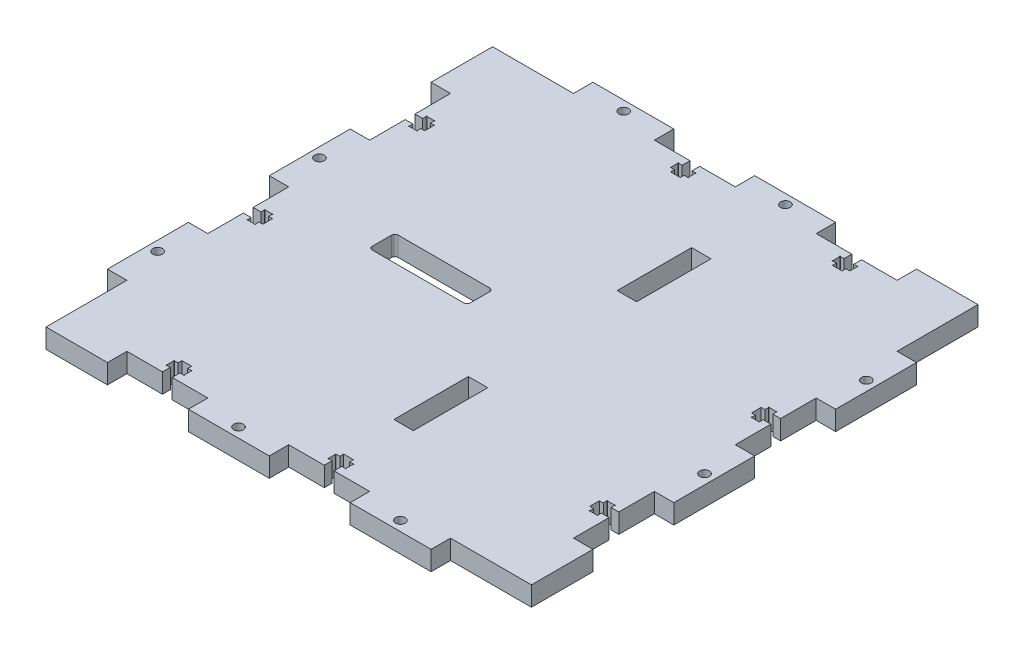
SolidWorks part; units mm, degrees
ref_plane "Front Plane" through (0, 0, 0) normal (0, 0, 1) x (1, 0, 0)
ref_plane "Top Plane" through (0, 0, 0) normal (0, 1, 0) x (1, 0, 0)
ref_plane "Right Plane" through (0, 0, 0) normal (1, 0, 0) x (0, 0, -1)
sketch "Sketch1" plane through (0, 0, 0) normal (0, 1, 0) x (1, 0, 0)
  line L0 (0, 75) -> (25, 75)
  line L1 (-50, 75) -> (-25, 75)
  line L2 (-75, 69) -> (-75, 50)
  line L3 (-69, -75) -> (-50, -75)
  line L4 (75, 50) -> (75, 25)
  line L7 (-75, 69) -> (-50, 69)
  line L8 (-50, 75) -> (-50, 69)
  line L10 (-25, 75) -> (-25, 69)
  line L11 (-25, 69) -> (0, 69)
  line L12 (0, 75) -> (0, 69)
  line L13 (50, 75) -> (69, 75)
  line L15 (25, 75) -> (25, 69)
  line L16 (25, 69) -> (50, 69)
  line L17 (50, 75) -> (50, 69)
  line L18 (75, 0) -> (75, -25)
  line L21 (75, 50) -> (69, 50)
  line L22 (69, 75) -> (69, 50)
  line L23 (75, 25) -> (69, 25)
  line L25 (75, 0) -> (69, 0)
  line L26 (69, 25) -> (69, 0)
  line L27 (75, -25) -> (69, -25)
  line L29 (75, -50) -> (69, -50)
  line L30 (69, -25) -> (69, -50)
  line L31 (75, -50) -> (75, -69)
  line L32 (25, -75) -> (50, -75)
  line L35 (75, -69) -> (50, -69)
  line L36 (50, -75) -> (50, -69)
  line L38 (25, -75) -> (25, -69)
  line L39 (25, -69) -> (0, -69)
  line L40 (0, -75) -> (0, -69)
  line L42 (-25, -75) -> (-25, -69)
  line L43 (-25, -69) -> (-50, -69)
  line L44 (-50, -75) -> (-50, -69)
  line L45 (-25, -75) -> (0, -75)
  line L46 (-75, 25) -> (-75, 0)
  line L49 (-75, -50) -> (-69, -50)
  line L50 (-69, -75) -> (-69, -50)
  line L51 (-75, -25) -> (-69, -25)
  line L53 (-75, 0) -> (-69, 0)
  line L54 (-69, -25) -> (-69, 0)
  line L55 (-75, 25) -> (-69, 25)
  line L57 (-75, 50) -> (-69, 50)
  line L58 (-69, 25) -> (-69, 50)
  line L59 (-75, -25) -> (-75, -50)
  dimension "D1" = 150
  dimension "D2" = 150
  dimension "D3" = 25
  dimension "D4" = 6
  dimension "D5" = 25
  dimension "25" = 25
  dimension "D6" = 25
  dimension "D7" = 6
  dimension "D8" = 6
  dimension "D9" = 25
  dimension "D10" = 25
  dimension "D11" = 6
  dimension "D12" = 25
  dimension "D13" = 6
  dimension "D14" = 25
  dimension "D15" = 25
  dimension "D16" = 6
  dimension "D17" = 25
  dimension "D18" = 19
  dimension "D19" = 6
  dimension "D20" = 25
  dimension "D21" = 25
  dimension "D22" = 25
  dimension "D23" = 6
  dimension "D24" = 6
  dimension "D25" = 25
  dimension "D26" = 25
  dimension "D27" = 19
  dimension "D28" = 6
  dimension "D29" = 25
  dimension "D30" = 25
  dimension "D31" = 6
  dimension "D32" = 25
  dimension "D33" = 25
  dimension "D34" = 6
  dimension "D35" = 25
  dimension "D36" = 19
extrude "Boss-Extrude1" add sketch "Sketch1" along normal blind 6
sketch "Sketch2" plane through (0, 6, 0) normal (0, 1, 0) x (1, 0, 0)
  line L0 (-25, 75) -> (-50, 75) construction
  line L1 (-25, 69) -> (-25, 75) construction
  line L2 (25, 75) -> (0, 75) construction
  line L3 (25, 69) -> (25, 75) construction
  line L4 (75, 25) -> (75, 50) construction
  line L5 (75, 50) -> (69, 50) construction
  line L6 (75, -25) -> (75, 0) construction
  line L7 (75, 0) -> (69, 0) construction
  line L8 (25, -75) -> (50, -75) construction
  line L9 (50, -75) -> (50, -69) construction
  line L10 (-25, -75) -> (0, -75) construction
  line L11 (0, -75) -> (0, -69) construction
  line L12 (-69, -25) -> (-75, -25) construction
  line L13 (-75, -25) -> (-75, -50) construction
  line L14 (-75, 25) -> (-75, 0) construction
  line L15 (-75, 0) -> (-69, 0) construction
  line L16 (-11, 69) -> (-14, 69)
  line L59 (0, 69) -> (-25, 69) construction
  line L60 (-14, 69) -> (-14, 66.6)
  line L61 (-14, 66.6) -> (-15.1, 66.6)
  line L63 (-15.2, 66.5) -> (-15.2, 64.3)
  line L65 (-15.1, 64.2) -> (-14, 64.2)
  line L66 (-14, 64.2) -> (-14, 63)
  line L67 (-14, 63) -> (-11, 63)
  line L69 (-12.5, 69) -> (-12.5, 63) construction
  line L72 (-11, 64.2) -> (-11, 63)
  line L73 (-9.9, 64.2) -> (-11, 64.2)
  line L74 (-9.8, 66.5) -> (-9.8, 64.3)
  line L75 (-11, 66.6) -> (-9.9, 66.6)
  line L76 (-11, 69) -> (-11, 66.6)
  line L91 (69, 11) -> (69, 14)
  line L92 (69, 14) -> (66.6, 14)
  line L93 (66.6, 14) -> (66.6, 15.1)
  line L94 (66.5, 15.2) -> (64.3, 15.2)
  line L95 (64.2, 15.1) -> (64.2, 14)
  line L96 (64.2, 14) -> (63, 14)
  line L97 (63, 14) -> (63, 11)
  line L98 (69, 12.5) -> (63, 12.5) construction
  line L99 (64.2, 11) -> (63, 11)
  line L100 (64.2, 9.9) -> (64.2, 11)
  line L101 (66.5, 9.8) -> (64.3, 9.8)
  line L102 (66.6, 11) -> (66.6, 9.9)
  line L103 (69, 11) -> (66.6, 11)
  line L104 (69, 0) -> (69, 25) construction
  line L105 (39, 69) -> (36, 69)
  line L106 (36, 69) -> (36, 66.6)
  line L107 (36, 66.6) -> (34.9, 66.6)
  line L108 (34.8, 66.5) -> (34.8, 64.3)
  line L109 (34.9, 64.2) -> (36, 64.2)
  line L110 (36, 64.2) -> (36, 63)
  line L111 (36, 63) -> (39, 63)
  line L112 (37.5, 69) -> (37.5, 63) construction
  line L113 (39, 64.2) -> (39, 63)
  line L114 (40.1, 64.2) -> (39, 64.2)
  line L115 (40.2, 66.5) -> (40.2, 64.3)
  line L116 (39, 66.6) -> (40.1, 66.6)
  line L117 (39, 69) -> (39, 66.6)
  line L118 (50, 69) -> (25, 69) construction
  line L119 (69, -39) -> (69, -36)
  line L120 (69, -36) -> (66.6, -36)
  line L121 (66.6, -36) -> (66.6, -34.9)
  line L122 (66.5, -34.8) -> (64.3, -34.8)
  line L123 (64.2, -34.9) -> (64.2, -36)
  line L124 (64.2, -36) -> (63, -36)
  line L125 (63, -36) -> (63, -39)
  line L126 (69, -37.5) -> (63, -37.5) construction
  line L127 (64.2, -39) -> (63, -39)
  line L128 (64.2, -40.1) -> (64.2, -39)
  line L129 (66.5, -40.2) -> (64.3, -40.2)
  line L130 (66.6, -39) -> (66.6, -40.1)
  line L131 (69, -39) -> (66.6, -39)
  line L132 (69, -50) -> (69, -25) construction
  line L133 (11, -69) -> (14, -69)
  line L134 (14, -69) -> (14, -66.6)
  line L135 (14, -66.6) -> (15.1, -66.6)
  line L136 (15.2, -66.5) -> (15.2, -64.3)
  line L137 (15.1, -64.2) -> (14, -64.2)
  line L138 (14, -64.2) -> (14, -63)
  line L139 (14, -63) -> (11, -63)
  line L140 (12.5, -69) -> (12.5, -63) construction
  line L141 (11, -64.2) -> (11, -63)
  line L142 (9.9, -64.2) -> (11, -64.2)
  line L143 (9.8, -66.5) -> (9.8, -64.3)
  line L144 (11, -66.6) -> (9.9, -66.6)
  line L145 (11, -69) -> (11, -66.6)
  line L146 (0, -69) -> (25, -69) construction
  line L147 (-39, -69) -> (-36, -69)
  line L148 (-36, -69) -> (-36, -66.6)
  line L149 (-36, -66.6) -> (-34.9, -66.6)
  line L150 (-34.8, -66.5) -> (-34.8, -64.3)
  line L151 (-34.9, -64.2) -> (-36, -64.2)
  line L152 (-36, -64.2) -> (-36, -63)
  line L153 (-36, -63) -> (-39, -63)
  line L154 (-37.5, -69) -> (-37.5, -63) construction
  line L155 (-39, -64.2) -> (-39, -63)
  line L156 (-40.1, -64.2) -> (-39, -64.2)
  line L157 (-40.2, -66.5) -> (-40.2, -64.3)
  line L158 (-39, -66.6) -> (-40.1, -66.6)
  line L159 (-39, -69) -> (-39, -66.6)
  line L160 (-50, -69) -> (-25, -69) construction
  line L161 (-69, 39) -> (-69, 36)
  line L162 (-69, 36) -> (-66.6, 36)
  line L163 (-66.6, 36) -> (-66.6, 34.9)
  line L164 (-66.5, 34.8) -> (-64.3, 34.8)
  line L165 (-64.2, 34.9) -> (-64.2, 36)
  line L166 (-64.2, 36) -> (-63, 36)
  line L167 (-63, 36) -> (-63, 39)
  line L168 (-69, 37.5) -> (-63, 37.5) construction
  line L169 (-64.2, 39) -> (-63, 39)
  line L170 (-64.2, 40.1) -> (-64.2, 39)
  line L171 (-66.5, 40.2) -> (-64.3, 40.2)
  line L172 (-66.6, 39) -> (-66.6, 40.1)
  line L173 (-69, 39) -> (-66.6, 39)
  line L174 (-69, 50) -> (-69, 25) construction
  line L175 (-69, -11) -> (-69, -14)
  line L176 (-69, -14) -> (-66.6, -14)
  line L177 (-66.6, -14) -> (-66.6, -15.1)
  line L178 (-66.5, -15.2) -> (-64.3, -15.2)
  line L179 (-64.2, -15.1) -> (-64.2, -14)
  line L180 (-64.2, -14) -> (-63, -14)
  line L181 (-63, -14) -> (-63, -11)
  line L182 (-69, -12.5) -> (-63, -12.5) construction
  line L183 (-64.2, -11) -> (-63, -11)
  line L184 (-64.2, -9.9) -> (-64.2, -11)
  line L185 (-66.5, -9.8) -> (-64.3, -9.8)
  line L186 (-66.6, -11) -> (-66.6, -9.9)
  line L187 (-69, -11) -> (-66.6, -11)
  line L188 (-69, 0) -> (-69, -25) construction
  circle A0 centre (-37.5, 72) radius 1.5
  circle A1 centre (12.5, 72) radius 1.5
  circle A2 centre (72, 37.5) radius 1.5
  circle A3 centre (72, -12.5) radius 1.5
  circle A4 centre (37.5, -72) radius 1.5
  circle A5 centre (-12.5, -72) radius 1.5
  circle A6 centre (-72, -37.5) radius 1.5
  circle A7 centre (-72, 12.5) radius 1.5
  arc A9 (-15.1, 66.6) -> (-15.2, 66.5) centre (-15.2, 66.6) ccw
  arc A10 (-15.2, 64.3) -> (-15.1, 64.2) centre (-15.2, 64.2) ccw
  arc A11 (-9.8, 64.3) -> (-9.9, 64.2) centre (-9.8, 64.2) cw
  arc A12 (-9.9, 66.6) -> (-9.8, 66.5) centre (-9.8, 66.6) cw
  arc A17 (66.6, 15.1) -> (66.5, 15.2) centre (66.6, 15.2) ccw
  arc A18 (64.3, 15.2) -> (64.2, 15.1) centre (64.2, 15.2) ccw
  arc A19 (64.3, 9.8) -> (64.2, 9.9) centre (64.2, 9.8) cw
  arc A20 (66.6, 9.9) -> (66.5, 9.8) centre (66.6, 9.8) cw
  arc A21 (34.9, 66.6) -> (34.8, 66.5) centre (34.8, 66.6) ccw
  arc A22 (34.8, 64.3) -> (34.9, 64.2) centre (34.8, 64.2) ccw
  arc A23 (40.2, 64.3) -> (40.1, 64.2) centre (40.2, 64.2) cw
  arc A24 (40.1, 66.6) -> (40.2, 66.5) centre (40.2, 66.6) cw
  arc A25 (66.6, -34.9) -> (66.5, -34.8) centre (66.6, -34.8) ccw
  arc A26 (64.3, -34.8) -> (64.2, -34.9) centre (64.2, -34.8) ccw
  arc A27 (64.3, -40.2) -> (64.2, -40.1) centre (64.2, -40.2) cw
  arc A28 (66.6, -40.1) -> (66.5, -40.2) centre (66.6, -40.2) cw
  arc A29 (15.1, -66.6) -> (15.2, -66.5) centre (15.2, -66.6) ccw
  arc A30 (15.2, -64.3) -> (15.1, -64.2) centre (15.2, -64.2) ccw
  arc A31 (9.8, -64.3) -> (9.9, -64.2) centre (9.8, -64.2) cw
  arc A32 (9.9, -66.6) -> (9.8, -66.5) centre (9.8, -66.6) cw
  arc A33 (-34.9, -66.6) -> (-34.8, -66.5) centre (-34.8, -66.6) ccw
  arc A34 (-34.8, -64.3) -> (-34.9, -64.2) centre (-34.8, -64.2) ccw
  arc A35 (-40.2, -64.3) -> (-40.1, -64.2) centre (-40.2, -64.2) cw
  arc A36 (-40.1, -66.6) -> (-40.2, -66.5) centre (-40.2, -66.6) cw
  arc A37 (-66.6, 34.9) -> (-66.5, 34.8) centre (-66.6, 34.8) ccw
  arc A38 (-64.3, 34.8) -> (-64.2, 34.9) centre (-64.2, 34.8) ccw
  arc A39 (-64.3, 40.2) -> (-64.2, 40.1) centre (-64.2, 40.2) cw
  arc A40 (-66.6, 40.1) -> (-66.5, 40.2) centre (-66.6, 40.2) cw
  arc A41 (-66.6, -15.1) -> (-66.5, -15.2) centre (-66.6, -15.2) ccw
  arc A42 (-64.3, -15.2) -> (-64.2, -15.1) centre (-64.2, -15.2) ccw
  arc A43 (-64.3, -9.8) -> (-64.2, -9.9) centre (-64.2, -9.8) cw
  arc A44 (-66.6, -9.9) -> (-66.5, -9.8) centre (-66.6, -9.8) cw
  point P83 (-12.5, 69)
  point P104 (69, 12.5)
  point P122 (37.5, 69)
  point P148 (69, -37.5)
  point P174 (12.5, -69)
  point P196 (-37.5, -69)
  point P222 (-69, 37.5)
  point P246 (-69, -12.5)
  dimension "D1" = 3
  dimension "D3" = 3
  dimension "D5" = 3
  dimension "D7" = 3
  dimension "D9" = 3
  dimension "D11" = 3
  dimension "D13" = 12.5
  dimension "D15" = 3
  dimension "D32" = 3
  dimension "D31" = 3
  dimension "D17" = 3
  dimension "D29" = 3
  dimension "D30" = 3
  dimension "D33" = 3
  dimension "D34" = 3
  dimension "D35" = 3
  dimension "D36" = 3
  dimension "D2" = 12.5
  dimension "D4" = 12.5
  dimension "D6" = 12.5
  dimension "D8" = 12.5
  dimension "D10" = 12.5
  dimension "D12" = 12.5
  dimension "D14" = 3
  dimension "D16" = 12.5
  dimension "D18" = 6
  dimension "D19" = 5.4
  dimension "D20" = 2.4
  dimension "D21" = 1.2
  dimension "D22" = 0.1
  dimension "D23" = 3
  dimension "D24" = 6
  dimension "D25" = 5.4
  dimension "D26" = 2.4
  dimension "D27" = 1.2
  dimension "D28" = 0.1
  dimension "D37" = 3
  dimension "D38" = 6
  dimension "D39" = 5.4
  dimension "D40" = 2.4
  dimension "D41" = 1.2
  dimension "D42" = 0.1
  dimension "D43" = 3
  dimension "D44" = 6
  dimension "D45" = 5.4
  dimension "D46" = 2.4
  dimension "D47" = 1.2
  dimension "D48" = 0.1
  dimension "D49" = 3
  dimension "D50" = 6
  dimension "D51" = 5.4
  dimension "D52" = 2.4
  dimension "D53" = 1.2
  dimension "D54" = 0.1
  dimension "D55" = 3
  dimension "D56" = 6
  dimension "D57" = 5.4
  dimension "D58" = 2.4
  dimension "D59" = 1.2
  dimension "D60" = 0.1
  dimension "D61" = 3
  dimension "D62" = 6
  dimension "D63" = 5.4
  dimension "D64" = 2.4
  dimension "D65" = 1.2
  dimension "D66" = 0.1
  dimension "D67" = 3
  dimension "D68" = 6
  dimension "D69" = 5.4
  dimension "D70" = 2.4
  dimension "D71" = 1.2
  dimension "D72" = 0.1
extrude "Cut-Extrude1" cut sketch "Sketch2" against normal through all
sketch "Sketch3" plane through (0, 0, 0) normal (0, -1, 0) x (1, 0, 0)
  line L0 (12.5, 63) -> (12.5, -75) construction
  line L1 (14, 63) -> (11, 63) construction
  line L2 (25, -75) -> (0, -75) construction
  line L3 (69, 0) -> (-69, 0) construction
  line L4 (15.5, 46) -> (9.5, 46)
  line L9 (9.5, 46) -> (9.5, 23)
  line L10 (9.5, 23) -> (15.5, 23)
  line L15 (15.5, 23) -> (15.5, 46)
  line L16 (9.5, -46) -> (9.5, -23)
  line L17 (15.5, -46) -> (9.5, -46)
  line L18 (15.5, -23) -> (15.5, -46)
  line L19 (9.5, -23) -> (15.5, -23)
  point P13 (12.5, 46)
  dimension "D1" = 23
  dimension "D2" = 6
  dimension "D3" = 23
extrude "Cut-Extrude2" cut sketch "Sketch3" against normal through all
sketch "Sketch4" plane through (0, 0, 0) normal (0, -1, 0) x (1, 0, 0)
  line L0 (0, 0) -> (-69, 0) construction
  line L1 (-40.2, 64.3) -> (-40.2, 0) construction
  line L2 (-9.9, -64.2) -> (-9.9, 0) construction
  line L3 (-40.2, -4) -> (-40.2, 4)
  line L4 (-40.2, 4) -> (-9.9, 4)
  line L5 (-9.9, 4) -> (-9.9, -4)
  line L6 (-40.2, -4) -> (-9.9, -4)
  dimension "D1" = 4
extrude "Cut-Extrude3" cut sketch "Sketch4" against normal through all
fillet "Fillet1" radius 1 4 edges at (-40.2, 3, -4) (-40.2, 3, 4) (-9.9, 3, 4) (-9.9, 3, -4)
